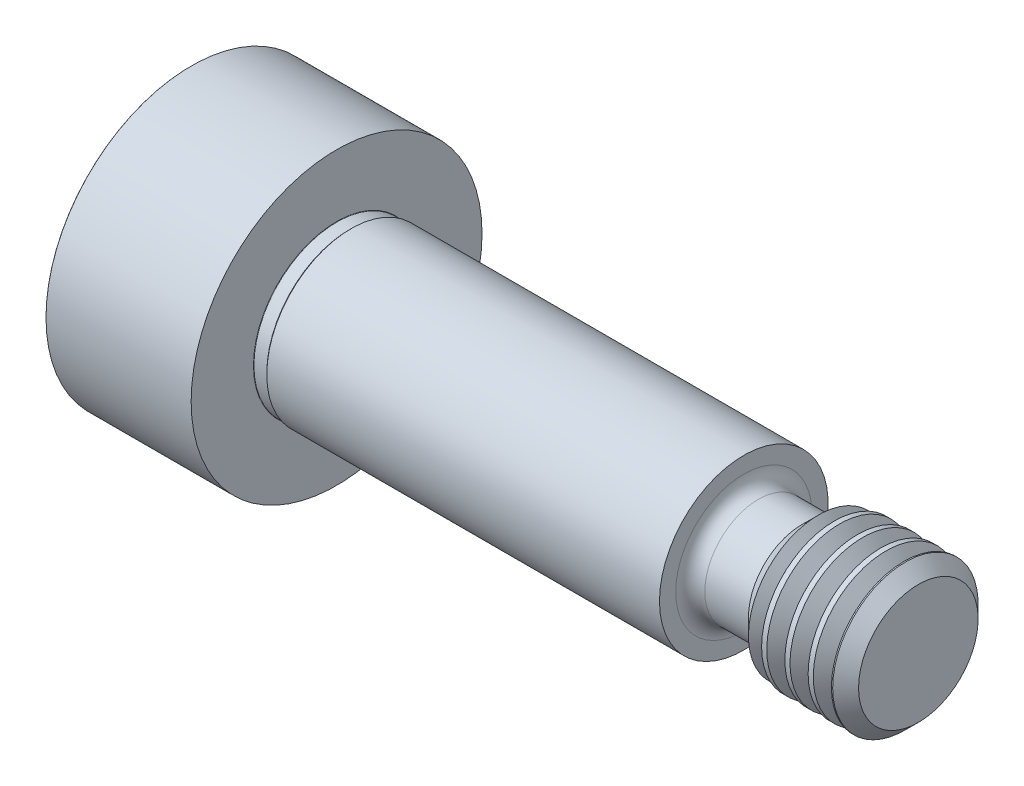
SolidWorks part; units mm, degrees
ref_plane "Plane1" through (0, 0, 0) normal (0, 0, 1) x (1, 0, 0)
ref_plane "Plane2" through (0, 0, 0) normal (0, 1, 0) x (1, 0, 0)
ref_plane "Plane3" through (0, 0, 0) normal (1, 0, 0) x (0, 0, -1)
sketch "BodySke" plane through (0, 0, 0) normal (0, 0, 1) x (1, 0, 0)
  line L0 (0, 0) -> (0, 5)
  line L2 (0, 5) -> (5, 5)
  line L3 (5, 5) -> (5, 2.86)
  line L4 (5.01, 2.85) -> (5.45, 2.85)
  line L5 (5.45, 2.85) -> (5.5, 2.9)
  line L6 (5.5, 2.9) -> (19, 2.9)
  line L7 (19, 2.9) -> (19, 2.34)
  line L8 (19.5, 1.84) -> (21, 1.84)
  line L9 (21, 1.84) -> (21.66, 2.5)
  line L10 (21.66, 2.5) -> (24.555, 2.5)
  line L11 (24.555, 2.5) -> (25, 2.055)
  line L12 (25, 2.055) -> (25, 0)
  line L13 (25, 0) -> (0, 0)
  line L14 (-6.35, 0) -> (107.95, 0) construction
  line L15 (24.555, -2.5) -> (25, -2.055) construction
  line L16 (19, -1.84) -> (21, -1.84) construction
  line L17 (5.5, -2.9) -> (19, -2.9) construction
  line L18 (5, -2.85) -> (5.45, -2.85) construction
  line L20 (21.8, 6.6914) -> (21.8, -10.6614) construction
  line L21 (19, 5.8311) -> (19, -10.0185) construction
  arc A0 (19, 2.34) -> (19.5, 1.84) centre (19.5, 2.34) ccw
  arc A1 (5.01, 2.85) -> (5, 2.86) centre (5.01, 2.86) cw
  point P29 (19, 1.84)
  point P32 (5, 2.85)
  dimension "Thread_neck_fillet_rad" = 0.5
  dimension "Head_fillet_radius" = 0.01
  dimension "Head_dia" = 10
  dimension "Head_ht" = 5
  dimension "Shoulder_neck_dia" = 5.7
  dimension "Diameter" = 5.8
  dimension "Thread_dia" = 5
  dimension "Minor_dia" = 4.11
  dimension "Thread_ch_ang" = 45
  dimension "Thread_neck_dia" = 3.68
  dimension "D11" = 45
  dimension "Thread_length" = 6
  dimension "D13" = 45
  dimension "Length" = 14
  dimension "Thread_neck_width" = 2
  dimension "Shoulder_neck_width" = 0.5
  dimension "Advance" = 0.8
  dimension "Thread_nom" = 6
  dimension "Thread_lim" = 3.2
revolve "BaseBody" add sketch "BodySke" angle 360 about L14
cosmetic thread "ThreadCosmetic" [suppressed] parameters "Thread_length"=3.2, "Thread_minor"=4.11
chamfer "Chamfer1" distance 0.01 1 edges at (0, 0, 5)
sketch "Sketch2" plane through (0, 0, 0) normal (0, 0, 1) x (1, 0, 0)
  line L0 (0, 1.54) -> (2.4, 1.54)
  line L1 (2.4, 1.54) -> (3.2891, 0)
  line L3 (3.2891, 0) -> (0, 0)
  line L4 (0, 0) -> (0, 1.54)
  line L5 (0, -1.54) -> (2.4, -1.54) construction
  line L6 (0, 0) -> (47.625, 0) construction
  dimension "D2" = 60
  dimension "PreBroach_depth" = 2.4
  dimension "PreBroach_dia" = 3.08
revolve "PreBroach" cut sketch "Sketch2" angle 360 about L6
sketch "Sketch3" plane through (0, 0, 0) normal (-1, 0, 0) x (0, 0, 1)
  line L0 (-1.54, -0.8891) -> (-1.54, 0.8891)
  line L1 (-1.54, 0.8891) -> (0, 1.7782)
  line L2 (0, 1.7782) -> (1.54, 0.8891)
  line L3 (1.54, 0.8891) -> (1.54, -0.8891)
  line L4 (1.54, -0.8891) -> (0, -1.7782)
  line L5 (0, -1.7782) -> (-1.54, -0.8891)
  dimension "D1" = 1.54
  dimension "Hex_size" = 3.08
  dimension "D2" = 1.54
  dimension "D3" = 120
  dimension "D4" = 3.08
extrude "Hex" cut sketch "Sketch3" against normal blind 2.4
sketch "ThdSchSke" plane through (0, 0, 0) normal (0, 0, 1) x (1, 0, 0)
  line L0 (21.8, -2.055) -> (21.2083, -2.9)
  line L1 (21.8, -2.055) -> (22.3917, -2.9)
  line L2 (22.3917, -2.9) -> (22.3917, -3.625)
  line L3 (-3.175, 0) -> (5.1513, 0) construction
  line L5 (22.3917, -3.625) -> (21.2083, -3.625)
  line L6 (21.2083, -3.625) -> (21.2083, -2.9)
  dimension "Thread_minor" = 4.11
  dimension "Diameter" = 5.8
  dimension "Start" = 21.8
  dimension "SideAngle" = 55
  dimension "VeeAngle" = 70
  dimension "Overcut" = 7.25
revolve "ThreadSchematic" cut sketch "ThdSchSke" angle 360 about L3
pattern_linear "ThdSchPat" count 4 spacing 0.8 along (1, 0, 0) of "ThreadSchematic"
equation "\"Thread_minor@ThreadCosmetic\" = \"Minor_dia@BodySke\""
equation "\"D1@Sketch3\" = \"Hex_size@Sketch3\" / 2"
equation "\"D2@Sketch3\" = \"D1@Sketch3\""
equation "\"D4@Sketch3\" = \"Hex_size@Sketch3\""
equation "\"Width@Chamfer1\" = \"Head_fillet_radius@BodySke\""
equation "\"Thread_length@ThreadCosmetic\" = ((sgn( (\"Thread_length@BodySke\" - \"Advance@BodySke\" - \"Thread_neck_width@BodySke\" ) - \"Thread_nom@BodySke\" )-1)*( (\"Thread_length@BodySke\" - \"Advance@BodySke\" - \"Thread_neck_width@BodySke\" ) - \"Thread_nom@BodySke\" ))/-2+ \"Thread_nom@BodySke\""
equation "\"Thread_minor@ThdSchSke\" = \"Minor_dia@BodySke\""
equation "\"Diameter@ThdSchSke\" = \"Diameter@BodySke\""
equation "\"Overcut@ThdSchSke\" = \"Diameter@BodySke\" * 1.25"
equation "\"Start@ThdSchSke\" = \"Head_ht@BodySke\" + \"Length@BodySke\" + \"Thread_length@BodySke\" -  \"Thread_length@ThreadCosmetic\"  '---Non-countersunk---"
equation "\"Num_threads@ThdSchPat\" = int( \"Thread_length@ThreadCosmetic\" / \"Advance@BodySke\" + 0.999 ) + 1"
equation "\"Advance@ThdSchPat\" = \"Thread_length@ThreadCosmetic\" /  (\"Num_threads@ThdSchPat\" - 1) 'relax it"
equation "\"Num_threads@ThdSchPat\" = \"Num_threads@ThdSchPat\" - sgn( \"Num_threads@ThdSchPat\" - 1) '---chamfered tips only---"
